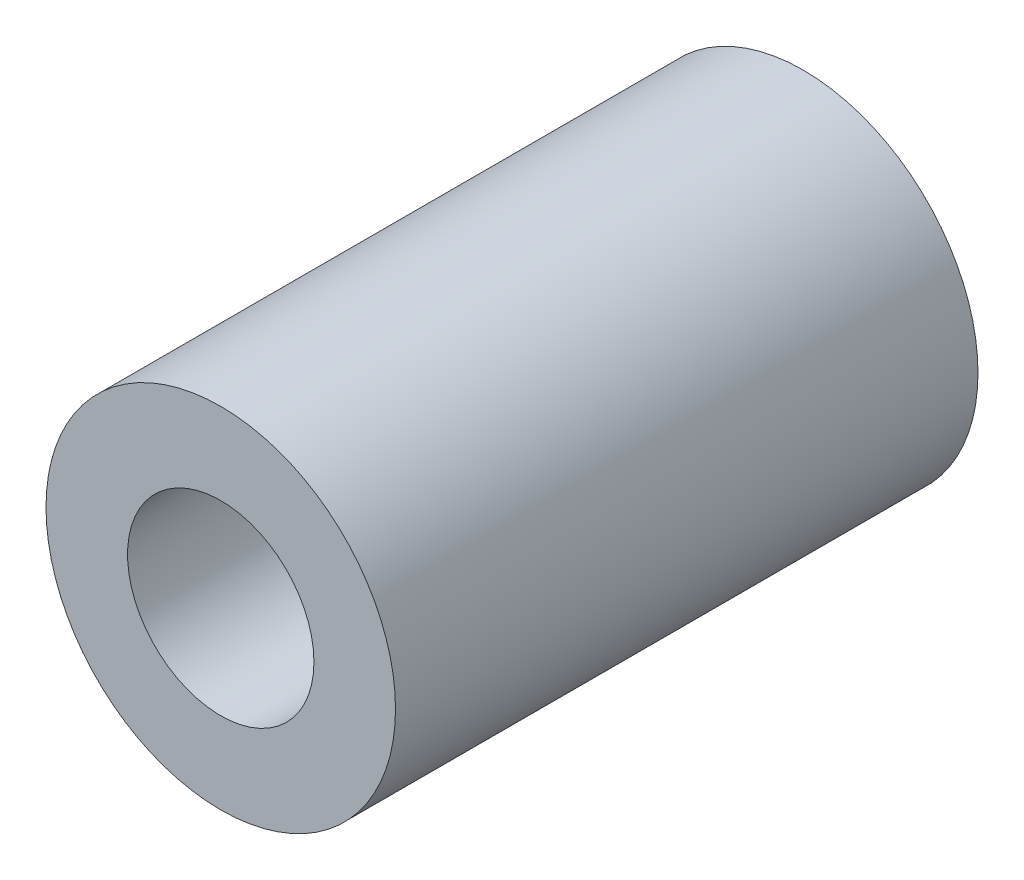
SolidWorks part; units mm, degrees
material "Nylon 6/10"
ref_plane "Front Plane" through (0, 0, 0) normal (0, 0, 1) x (1, 0, 0)
ref_plane "Top Plane" through (0, 0, 0) normal (0, 1, 0) x (1, 0, 0)
ref_plane "Right Plane" through (0, 0, 0) normal (1, 0, 0) x (0, 0, -1)
sketch "Sketch1" plane through (0, 0, 0) normal (0, 0, 1) x (1, 0, 0)
  circle A0 centre (0, 0) radius 3
  circle A1 centre (0, 0) radius 1.6
  dimension "OD" = 6
  dimension "ID" = 3.2
extrude "Extrude1" add sketch "Sketch1" along normal mid plane 10
sketch "Sketch2" plane through (0, 0, 0) normal (1, 0, 0) x (0, 0, -1)
  line L0 (-5, -1.6) -> (5, -1.6) construction
  line L3 (5, 1.6) -> (-5, 1.6) construction
  line L5 (-5, -1.6) -> (5, -1.6)
  line L6 (5, 1.6) -> (-5, 1.6)
sketch "Sketch4" plane through (0, 0, 5) normal (0, 0, 1) x (1, 0, 0)
  line L0 (0, 0) -> (-1.1314, 1.1314)
  line L1 (0, -55) -> (0, 55) construction
  circle A0 centre (0, 0) radius 1.6 construction
  dimension "D1" = 45
